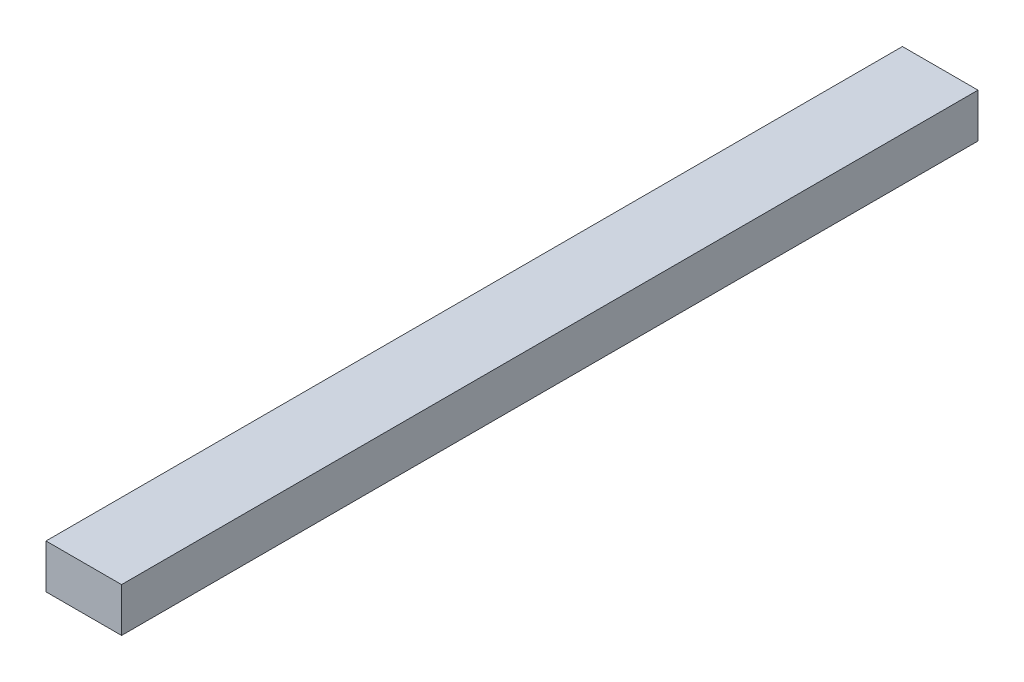
SolidWorks part; units mm, degrees
ref_plane "Front Plane" through (0, 0, 0) normal (0, 0, 1) x (1, 0, 0)
ref_plane "Top Plane" through (0, 0, 0) normal (0, 1, 0) x (1, 0, 0)
ref_plane "Right Plane" through (0, 0, 0) normal (1, 0, 0) x (0, 0, -1)
sketch "Sketch1" plane through (0, 0, 0) normal (0, 0, 1) x (1, 0, 0)
  line L1 (0, 0) -> (38.1, 0)
  line L2 (0, 0) -> (0, 22.225)
  line L3 (0, 22.225) -> (38.1, 22.225)
  line L4 (38.1, 0) -> (38.1, 22.225)
  dimension "D1" = 38.1
  dimension "D2" = 22.225
extrude "Boss-Extrude1" add sketch "Sketch1" along normal blind 431.8
